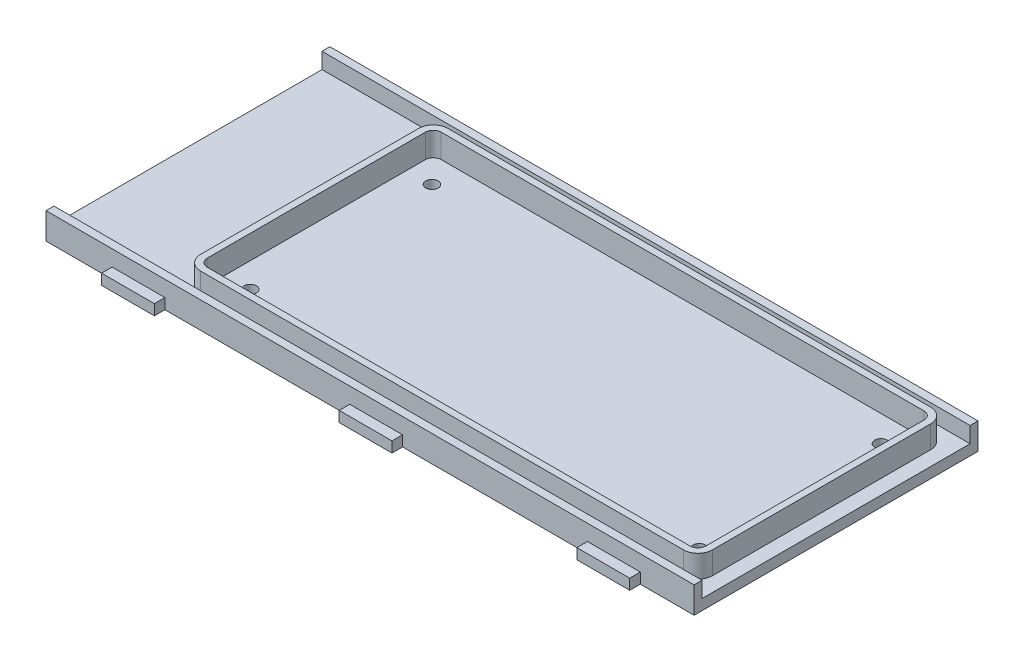
SolidWorks part; units mm, degrees
ref_plane "Front Plane" through (0, 0, 0) normal (0, 0, 1) x (1, 0, 0)
ref_plane "Top Plane" through (0, 0, 0) normal (0, 1, 0) x (1, 0, 0)
ref_plane "Right Plane" through (0, 0, 0) normal (1, 0, 0) x (0, 0, -1)
sketch "Sketch1" plane through (0, 0, 0) normal (0, 1, 0) x (1, 0, 0)
  line L0 (-61.35, 0) -> (61.35, 0) construction
  line L1 (-61.35, 26.875) -> (-48.84, 26.875)
  line L2 (-61.35, 26.875) -> (-61.35, -26.875)
  line L3 (-61.35, -26.875) -> (-48.84, -26.875)
  line L4 (61.35, 26.875) -> (61.35, -26.875)
  line L5 (-61.35, 26.875) -> (61.35, -26.875) construction
  line L6 (-61.35, -26.875) -> (61.35, 26.875) construction
  line L8 (-48.84, -26.875) -> (-48.84, -28.875)
  line L9 (-48.84, -28.875) -> (-38.84, -28.875)
  line L10 (-38.84, -26.875) -> (-38.84, -28.875)
  line L12 (-3.84, -26.875) -> (-3.84, -28.875)
  line L13 (-3.84, -28.875) -> (6.16, -28.875)
  line L14 (6.16, -26.875) -> (6.16, -28.875)
  line L16 (41.16, -26.875) -> (41.16, -28.875)
  line L17 (41.16, -28.875) -> (51.16, -28.875)
  line L18 (51.16, -26.875) -> (51.16, -28.875)
  line L19 (41.16, 28.875) -> (51.16, 28.875)
  line L20 (51.16, 26.875) -> (51.16, 28.875)
  line L22 (41.16, 26.875) -> (41.16, 28.875)
  line L23 (-3.84, 28.875) -> (6.16, 28.875)
  line L24 (6.16, 26.875) -> (6.16, 28.875)
  line L26 (-3.84, 26.875) -> (-3.84, 28.875)
  line L27 (-48.84, 28.875) -> (-38.84, 28.875)
  line L28 (-38.84, 26.875) -> (-38.84, 28.875)
  line L30 (-48.84, 26.875) -> (-48.84, 28.875)
  line L31 (-38.84, -26.875) -> (-3.84, -26.875)
  line L32 (6.16, -26.875) -> (41.16, -26.875)
  line L33 (51.16, -26.875) -> (61.35, -26.875)
  line L34 (51.16, 26.875) -> (61.35, 26.875)
  line L35 (6.16, 26.875) -> (41.16, 26.875)
  line L36 (-38.84, 26.875) -> (-3.84, 26.875)
  point P0 (0, 0)
  point P33 (0, 0)
  dimension "D1" = 53.75
  dimension "D2" = 122.7
  dimension "D3" = 10
  dimension "D4" = 10
  dimension "D5" = 10
  dimension "D6" = 2
  dimension "D7" = 2
  dimension "D8" = 2
  dimension "D9" = 12.51
  dimension "D10" = 35
  dimension "D11" = 35
extrude "Boss-Extrude1" add sketch "Sketch1" along normal blind 2
sketch "Sketch2" plane through (0, 2, 0) normal (0, 1, 0) x (1, 0, 0)
  line L0 (61.35, -26.875) -> (61.35, 26.875) construction
  line L1 (-61.35, 26.875) -> (61.35, 26.875)
  line L2 (-61.35, 26.875) -> (-61.35, 25.375)
  line L3 (-61.35, 25.375) -> (61.35, 25.375)
  line L4 (61.35, 26.875) -> (61.35, 25.375)
  line L5 (0, 0) -> (61.35, 0) construction
  line L6 (-61.35, -25.375) -> (61.35, -25.375)
  line L7 (61.35, -26.875) -> (61.35, -25.375)
  line L8 (-61.35, -26.875) -> (61.35, -26.875)
  line L9 (-61.35, -26.875) -> (-61.35, -25.375)
  dimension "D1" = 1.5
extrude "Boss-Extrude2" add sketch "Sketch2" along normal blind 3
sketch "Sketch3" plane through (0, 2, 0) normal (0, 1, 0) x (1, 0, 0)
  line L0 (-61.35, 0) -> (61.35, 0) construction
  line L1 (-35.55, 22.15) -> (55.85, 22.15)
  line L2 (-37.05, 20.65) -> (-37.05, -20.65)
  line L3 (-35.55, -22.15) -> (55.85, -22.15)
  line L4 (57.35, 20.65) -> (57.35, -20.65)
  line L5 (-37.05, 22.15) -> (57.35, -22.15) construction
  line L6 (-37.05, -22.15) -> (57.35, 22.15) construction
  line L7 (-61.35, 25.375) -> (-61.35, -25.375) construction
  line L8 (61.35, -25.375) -> (61.35, 25.375) construction
  line L9 (0, 25.375) -> (0, -25.375) construction
  line L10 (-61.35, 25.375) -> (61.35, 25.375) construction
  line L11 (61.35, -25.375) -> (-61.35, -25.375) construction
  arc A0 (55.85, 22.15) -> (57.35, 20.65) centre (55.85, 20.65) cw
  arc A1 (55.85, -22.15) -> (57.35, -20.65) centre (55.85, -20.65) ccw
  arc A2 (-35.55, -22.15) -> (-37.05, -20.65) centre (-35.55, -20.65) cw
  arc A3 (-37.05, 20.65) -> (-35.55, 22.15) centre (-35.55, 20.65) cw
  point P0 (10.15, 0)
  point P17 (9.0425, 0)
  dimension "D4" = 1.5
  dimension "D1" = 44.3
  dimension "D2" = 94.4
  dimension "D3" = 4
extrude "Cut-Extrude1" cut sketch "Sketch3" against normal blind 0.25
sketch "Sketch4" plane through (0, 2, 0) normal (0, 1, 0) x (1, 0, 0)
  line L4 (55.85, 22.15) -> (-35.55, 22.15)
  line L5 (-37.05, 20.65) -> (-37.05, -20.65)
  line L6 (-35.55, -22.15) -> (55.85, -22.15)
  line L7 (57.35, -20.65) -> (57.35, 20.65)
  line L8 (55.85, 23.4) -> (-35.55, 23.4)
  line L9 (-38.3, 20.65) -> (-38.3, -20.65)
  line L10 (-35.55, -23.4) -> (55.85, -23.4)
  line L11 (58.6, -20.65) -> (58.6, 20.65)
  line L12 (55.85, 23.4) -> (-35.55, 23.4)
  line L13 (-38.3, 20.65) -> (-38.3, -20.65)
  line L14 (-35.55, -23.4) -> (55.85, -23.4)
  line L15 (58.6, -20.65) -> (58.6, 20.65)
  arc A4 (57.35, 20.65) -> (55.85, 22.15) centre (55.85, 20.65) ccw
  arc A5 (-35.55, 22.15) -> (-37.05, 20.65) centre (-35.55, 20.65) ccw
  arc A6 (-37.05, -20.65) -> (-35.55, -22.15) centre (-35.55, -20.65) ccw
  arc A7 (55.85, -22.15) -> (57.35, -20.65) centre (55.85, -20.65) ccw
  arc A8 (58.6, 20.65) -> (55.85, 23.4) centre (55.85, 20.65) ccw
  arc A9 (-35.55, 23.4) -> (-38.3, 20.65) centre (-35.55, 20.65) ccw
  arc A10 (-38.3, -20.65) -> (-35.55, -23.4) centre (-35.55, -20.65) ccw
  arc A11 (55.85, -23.4) -> (58.6, -20.65) centre (55.85, -20.65) ccw
  arc A12 (58.6, 20.65) -> (55.85, 23.4) centre (55.85, 20.65) ccw
  arc A13 (-35.55, 23.4) -> (-38.3, 20.65) centre (-35.55, 20.65) ccw
  arc A14 (-38.3, -20.65) -> (-35.55, -23.4) centre (-35.55, -20.65) ccw
  arc A15 (55.85, -23.4) -> (58.6, -20.65) centre (55.85, -20.65) ccw
  dimension "D1" = 1.25
  dimension "D2" = 1.25
extrude "Boss-Extrude3" add sketch "Sketch4" along normal blind 4.25
sketch "Sketch5" plane through (0, 1.75, 0) normal (0, 1, 0) x (1, 0, 0)
  line L0 (-37.05, 0) -> (57.35, 0) construction
  line L1 (-32.35, 17.2) -> (52.65, 17.2) construction
  line L2 (-32.35, 17.2) -> (-32.35, -17.2) construction
  line L3 (-32.35, -17.2) -> (52.65, -17.2) construction
  line L4 (52.65, 17.2) -> (52.65, -17.2) construction
  line L5 (-32.35, 17.2) -> (52.65, -17.2) construction
  line L6 (-32.35, -17.2) -> (52.65, 17.2) construction
  line L7 (-37.05, 20.65) -> (-37.05, -20.65) construction
  line L8 (57.35, -20.65) -> (57.35, 20.65) construction
  line L9 (10.15, 22.15) -> (10.15, -22.15) construction
  line L10 (55.85, 22.15) -> (-35.55, 22.15) construction
  line L11 (-35.55, -22.15) -> (55.85, -22.15) construction
  circle A0 centre (-32.35, 17.2) radius 1.175
  circle A1 centre (52.65, 17.2) radius 1.175
  circle A2 centre (52.65, -17.2) radius 1.175
  circle A3 centre (-32.35, -17.2) radius 1.175
  point P0 (10.15, 0)
  dimension "D3" = 2.35
  dimension "D4" = 2.35
  dimension "D5" = 2.35
  dimension "D6" = 2.35
  dimension "D1" = 85
  dimension "D2" = 34.4
extrude "Cut-Extrude2" cut sketch "Sketch5" against normal through all
